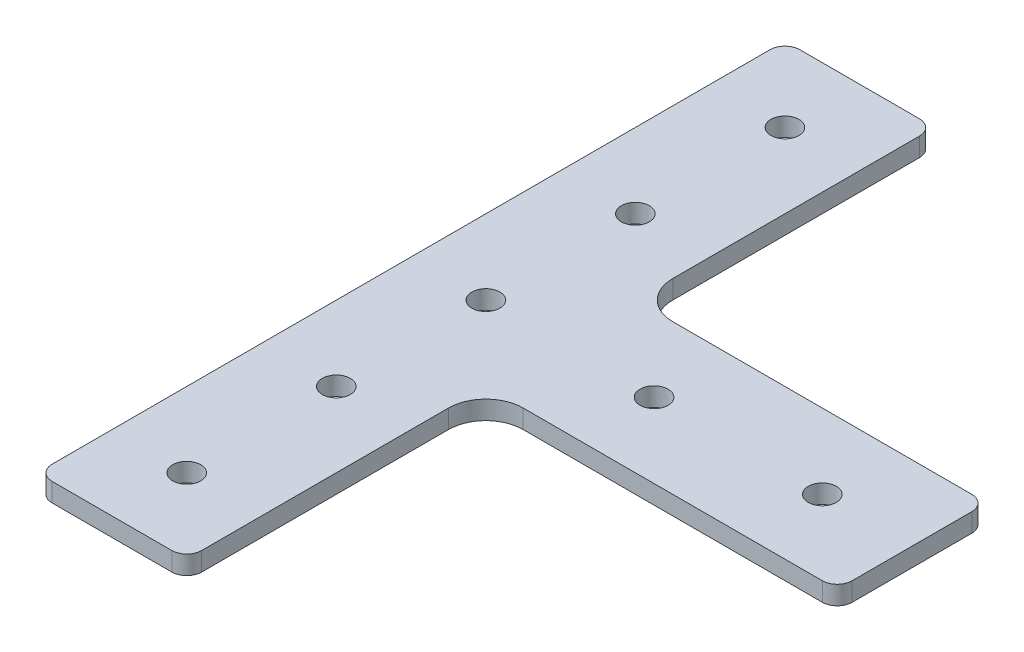
SolidWorks part; units mm, degrees
ref_plane "Front Plane" through (0, 0, 0) normal (0, 0, 1) x (1, 0, 0)
ref_plane "Top Plane" through (0, 0, 0) normal (0, 1, 0) x (1, 0, 0)
ref_plane "Right Plane" through (0, 0, 0) normal (1, 0, 0) x (0, 0, -1)
sketch "Sketch1" plane through (0, 0, 0) normal (0, 1, 0) x (1, 0, 0)
  line L0 (-12.7, -38.1) -> (-12.7, -35.56)
  line L2 (-12.7, -35.56) -> (-12.7, 35.56)
  line L3 (-10.16, 38.1) -> (10.16, 38.1)
  line L4 (12.7, -6.35) -> (12.7, 35.56)
  line L6 (12.7, -44.45) -> (12.7, -86.36)
  line L7 (19.05, -38.1) -> (69.85, -38.1)
  line L9 (19.05, -12.7) -> (69.85, -12.7)
  line L10 (72.39, -35.56) -> (72.39, -15.24)
  line L11 (10.16, -88.9) -> (-10.16, -88.9)
  line L12 (-12.7, -38.1) -> (-12.7, -86.36)
  line L13 (72.39, -25.4) -> (-12.7, -25.4) construction
  circle A0 centre (0, -25.4) radius 2.3813
  circle A1 centre (0, 0) radius 2.3813
  circle A2 centre (0, 25.4) radius 2.3813
  circle A3 centre (28.575, -25.4) radius 2.3813
  circle A4 centre (57.15, -25.4) radius 2.3812
  arc A5 (19.05, -12.7) -> (12.7, -6.35) centre (19.05, -6.35) cw
  arc A6 (12.7, 35.56) -> (10.16, 38.1) centre (10.16, 35.56) ccw
  arc A7 (-12.7, 35.56) -> (-10.16, 38.1) centre (-10.16, 35.56) cw
  arc A9 (69.85, -38.1) -> (72.39, -35.56) centre (69.85, -35.56) ccw
  arc A10 (72.39, -15.24) -> (69.85, -12.7) centre (69.85, -15.24) ccw
  arc A11 (12.7, -44.45) -> (19.05, -38.1) centre (19.05, -44.45) cw
  arc A12 (-10.16, -88.9) -> (-12.7, -86.36) centre (-10.16, -86.36) cw
  arc A13 (12.7, -86.36) -> (10.16, -88.9) centre (10.16, -86.36) cw
  circle A14 centre (0, -76.2) radius 2.3812
  circle A15 centre (0, -50.8) radius 2.3812
  point P0 (0, 0)
  point P23 (12.7, 38.1)
  point P26 (-12.7, 38.1)
  point P29 (-12.7, -38.1)
  point P32 (72.39, -38.1)
  point P35 (72.39, -12.7)
  point P41 (-12.7, -88.9)
  point P44 (12.7, -88.9)
  dimension "D5" = 4.7625
  dimension "D6" = 4.7625
  dimension "D7" = 4.7625
  dimension "D8" = 4.7625
  dimension "D9" = 4.7625
  dimension "D14" = 6.35
  dimension "D15" = 2.54
  dimension "D3" = 6.35
  dimension "D19" = 2.54
  dimension "D1" = 76.2
  dimension "D2" = 25.4
  dimension "D4" = 25.4
  dimension "D10" = 28.575
  dimension "D11" = 28.575
  dimension "D12" = 25.4
  dimension "D13" = 25.4
  dimension "D16" = 12.7
  dimension "D17" = 50.8
  dimension "D18" = 25.4
  dimension "D20" = 50.8
extrude "Boss-Extrude1" add sketch "Sketch1" along normal blind 3.175
